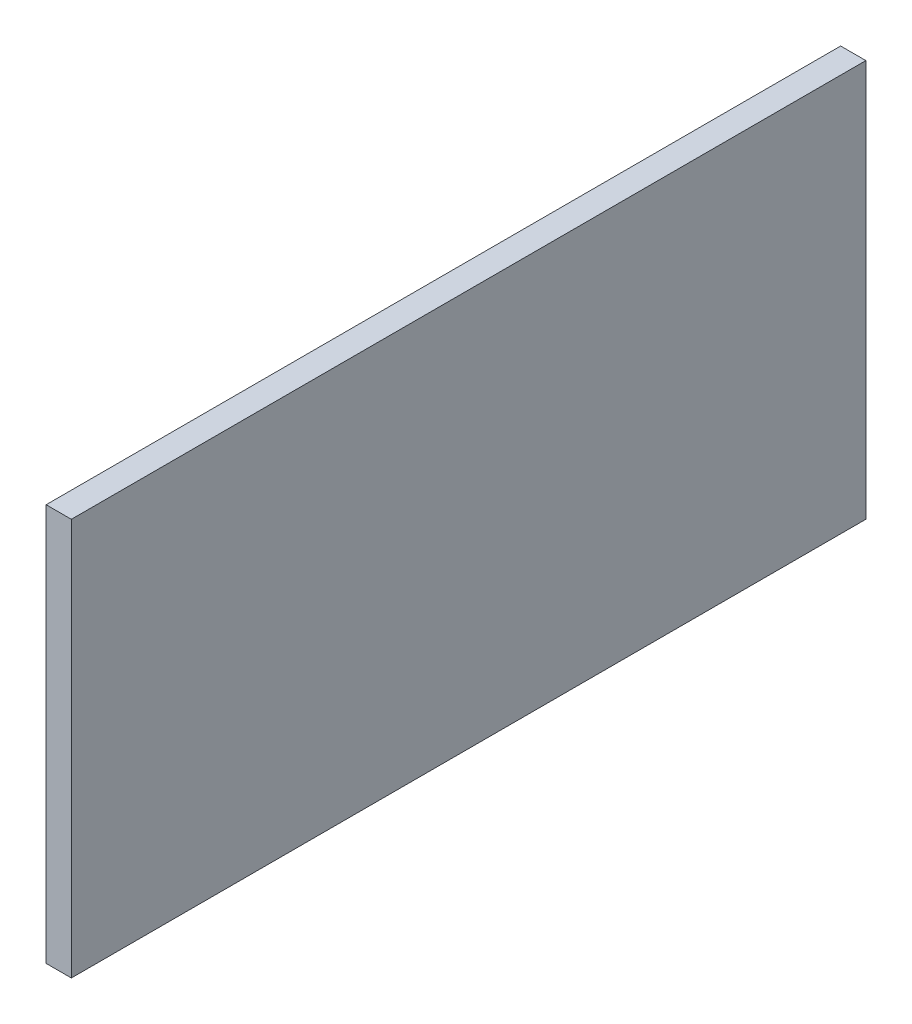
SolidWorks part; units mm, degrees
ref_plane "Front Plane" through (0, 0, 0) normal (0, 0, 1) x (1, 0, 0)
ref_plane "Top Plane" through (0, 0, 0) normal (0, 1, 0) x (1, 0, 0)
ref_plane "Right Plane" through (0, 0, 0) normal (1, 0, 0) x (0, 0, -1)
sketch "Sketch1" plane through (0, 0, 0) normal (1, 0, 0) x (0, 0, -1)
  line L1 (-10, 5) -> (10, 5)
  line L2 (-10, 5) -> (-10, -5)
  line L3 (-10, -5) -> (10, -5)
  line L4 (10, 5) -> (10, -5)
  line L5 (-10, 5) -> (10, -5) construction
  line L6 (-10, -5) -> (10, 5) construction
  point P0 (0, 0)
  dimension "D1" = 10
  dimension "D2" = 20
extrude "Boss-Extrude1" add sketch "Sketch1" along normal blind 0.635
